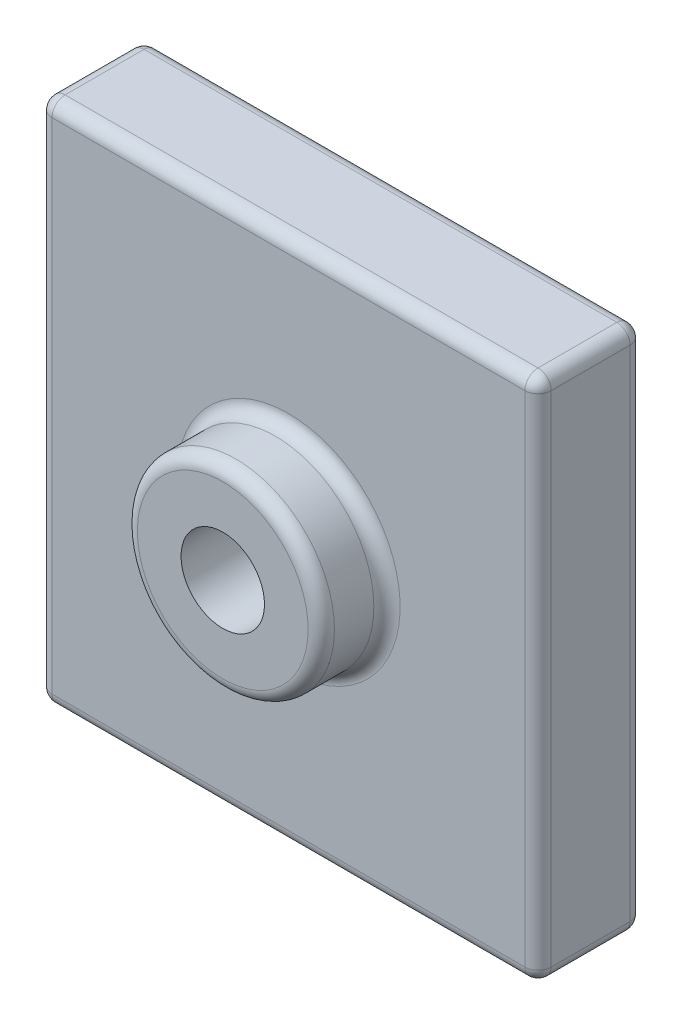
SolidWorks part; units mm, degrees
ref_plane "Front Plane" through (0, 0, 0) normal (0, 0, 1) x (1, 0, 0)
ref_plane "Top Plane" through (0, 0, 0) normal (0, 1, 0) x (1, 0, 0)
ref_plane "Right Plane" through (0, 0, 0) normal (1, 0, 0) x (0, 0, -1)
sketch "Sketch1" plane through (0, 0, 0) normal (0, 0, 1) x (1, 0, 0)
  line L1 (0, 0) -> (38, 0)
  line L2 (0, 0) -> (0, 40)
  line L3 (0, 40) -> (38, 40)
  line L4 (38, 0) -> (38, 40)
  dimension "D1" = 38
  dimension "D2" = 40
extrude "Boss-Extrude1" add sketch "Sketch1" along normal blind 8
sketch "Sketch2" plane through (0, 0, 8) normal (0, 0, 1) x (1, 0, 0)
  line L4 (0, 40) -> (0, 0)
  line L5 (0, 0) -> (38, 0)
  line L6 (38, 0) -> (38, 40)
  line L7 (38, 40) -> (0, 40)
  line L8 (0, 40) -> (0, 0) construction
  line L9 (0, 0) -> (38, 0) construction
  line L10 (38, 0) -> (38, 40) construction
  line L11 (38, 40) -> (0, 40) construction
  circle A0 centre (19, 20) radius 7.5
  circle A1 centre (19, 20) radius 3.175
  point P2 (19, 20)
  point P4 (0, 20)
  point P6 (19, 0)
  dimension "D2" = 15
  dimension "D3" = 6.35
  dimension "D1" = 0
extrude "Boss-Extrude2" add sketch "Sketch2" along normal blind 5
fillet "Fillet1" radius 1 14 edges at (26.5, 20, 13) (19, 0, 0) (19, 40, 0) (38, 0, 4) (38, 40, 4) (38, 20, 0) (0, 40, 4) (0, 0, 4) (0, 20, 0) (26.5, 20, 8) (19, 40, 8) (38, 20, 8) (19, 0, 8) (0, 20, 8)
sketch "Sketch3" plane through (0, 0, 0) normal (0, 0, -1) x (-1, 0, 0)
  line L4 (-1, 39) -> (-37, 39)
  line L5 (-37, 39) -> (-37, 1)
  line L6 (-37, 1) -> (-1, 1)
  line L7 (-1, 1) -> (-1, 39)
  line L8 (-1, 39) -> (-37, 39) construction
  line L9 (-37, 39) -> (-37, 1) construction
  line L10 (-37, 1) -> (-1, 1) construction
  line L11 (-1, 1) -> (-1, 39) construction
  line L15 (-15.792, 25.5565) -> (-22.208, 25.5565)
  line L16 (-22.208, 25.5565) -> (-25.4161, 20)
  line L17 (-25.4161, 20) -> (-22.208, 14.4435)
  line L18 (-22.208, 14.4435) -> (-15.792, 14.4435)
  line L19 (-15.792, 14.4435) -> (-12.5839, 20)
  line L20 (-12.5839, 20) -> (-15.792, 25.5565)
  circle A0 centre (-19, 20) radius 5.5565 construction
  point P2 (-19, 39)
  point P4 (-37, 20)
  point P6 (-19, 20)
  dimension "D2" = 11.113
  dimension "D1" = 0
extrude "Cut-Extrude1" cut sketch "Sketch3" against normal blind 5.5562
sketch "Sketch4" plane through (0, 0, 0) normal (0, 0, -1) x (-1, 0, 0)
  circle A0 centre (-19, 20) radius 3.175 construction
  circle A1 centre (-19, 20) radius 3.175
extrude "Cut-Extrude2" cut sketch "Sketch4" against normal through all
